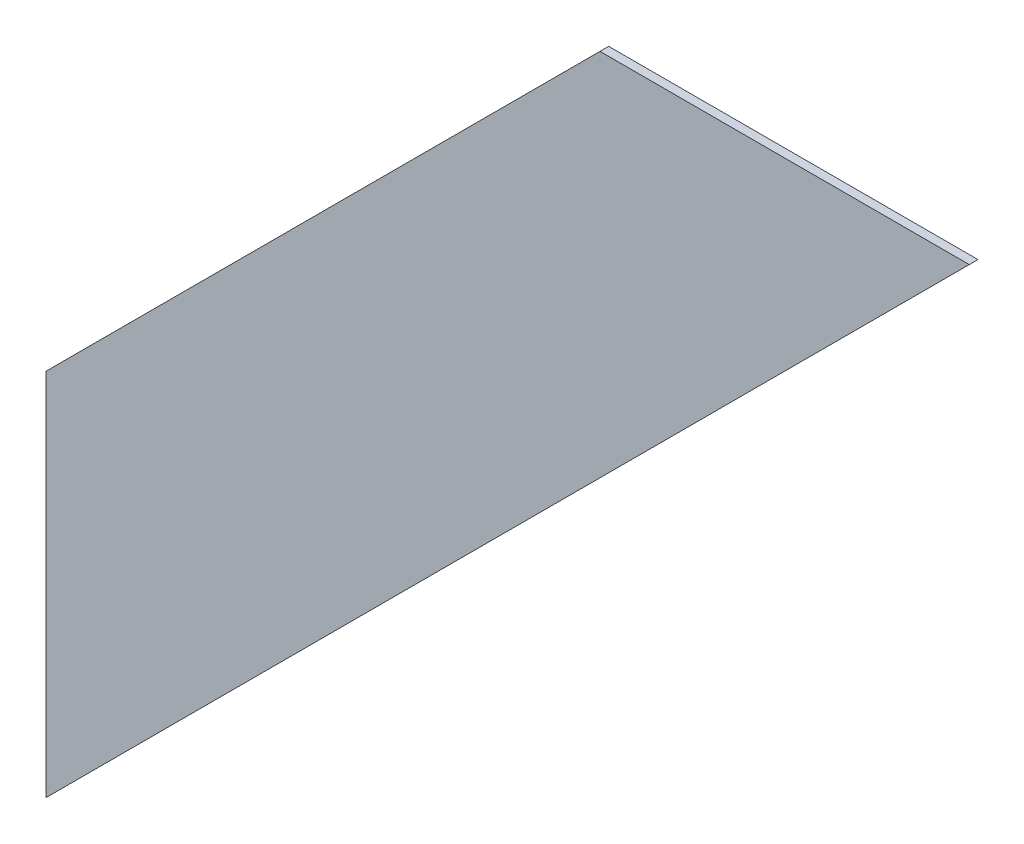
SolidWorks part; units mm, degrees
ref_plane "Front Plane" through (0, 0, 0) normal (0, 0, 1) x (1, 0, 0)
ref_plane "Top Plane" through (0, 0, 0) normal (0, 1, 0) x (1, 0, 0)
ref_plane "Right Plane" through (0, 0, 0) normal (1, 0, 0) x (0, 0, -1)
sketch "Sketch1" plane through (0, 0, 0) normal (0, 0, 1) x (1, 0, 0)
  line L0 (76.615, 25.9873) -> (-29.4511, -80.0788)
  line L1 (-29.4511, -80.0788) -> (76.615, -80.0788)
  line L2 (-29.4511, -80.0788) -> (-29.4511, 25.9873)
  line L3 (-29.4511, 25.9873) -> (76.615, 25.9873)
  line L4 (76.615, -80.0788) -> (76.615, 25.9873)
  line L5 (34.1885, 25.9873) -> (-29.4511, -37.6524)
  point P0 (0, 0)
  dimension "D1" = 150
  dimension "D2" = 30
extrude "Boss-Extrude1" add sketch "Sketch1" along normal blind 1 contours L3 L5 L2 L0
